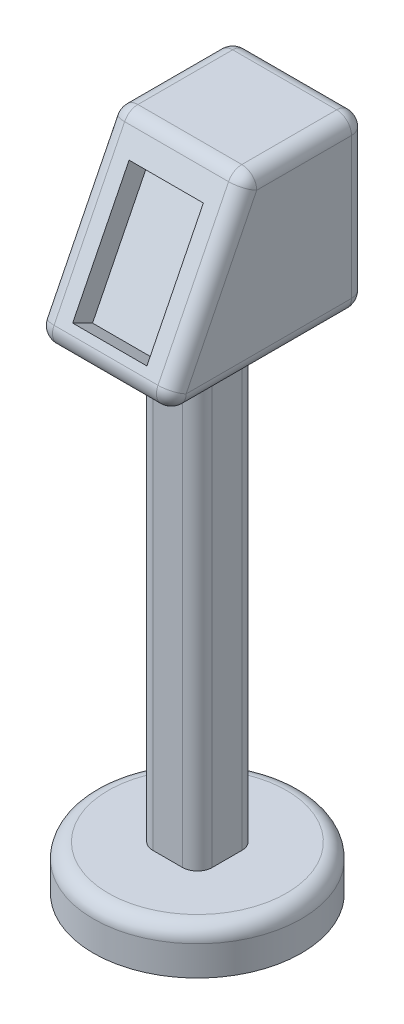
SolidWorks part; units mm, degrees
ref_plane "Front Plane" through (0, 0, 0) normal (0, 0, 1) x (1, 0, 0)
ref_plane "Top Plane" through (0, 0, 0) normal (0, 1, 0) x (1, 0, 0)
ref_plane "Right Plane" through (0, 0, 0) normal (1, 0, 0) x (0, 0, -1)
sketch "Sketch1" plane through (0, 0, 0) normal (0, 1, 0) x (1, 0, 0)
  circle A0 centre (0, 0) radius 140
  dimension "D1" = 280
extrude "Boss-Extrude1" add sketch "Sketch1" along normal blind 60
sketch "Sketch2" plane through (0, 60, 0) normal (0, 1, 0) x (1, 0, 0)
  line L1 (-40, 40) -> (40, 40)
  line L2 (-40, 40) -> (-40, -40)
  line L3 (-40, -40) -> (40, -40)
  line L4 (40, 40) -> (40, -40)
  line L5 (-40, 40) -> (40, -40) construction
  line L6 (-40, -40) -> (40, 40) construction
  point P0 (0, 0)
  dimension "D1" = 80
  dimension "D2" = 80
extrude "Boss-Extrude2" add sketch "Sketch2" along normal blind 600
sketch "Sketch3" plane through (0, 660, 0) normal (0, 1, 0) x (1, 0, 0)
  line L1 (-90, 137.5) -> (90, 137.5)
  line L2 (-90, 137.5) -> (-90, -137.5)
  line L3 (-90, -137.5) -> (90, -137.5)
  line L4 (90, 137.5) -> (90, -137.5)
  line L5 (-90, 137.5) -> (90, -137.5) construction
  line L6 (-90, -137.5) -> (90, 137.5) construction
  point P0 (0, 0)
  dimension "D1" = 275
  dimension "D2" = 180
extrude "Boss-Extrude3" add sketch "Sketch3" along normal blind 230
sketch "Sketch4" plane through (-90, 0, 0) normal (-1, 0, 0) x (0, 0, 1)
  line L0 (22.5, 890) -> (137.5, 660)
  line L1 (-137.5, 890) -> (137.5, 890) construction
  line L2 (137.5, 890) -> (137.5, 660) construction
  line L3 (137.5, 660) -> (137.5, 890)
  line L4 (137.5, 890) -> (22.5, 890)
  dimension "D1" = 160
  dimension "D2" = 0
extrude "Cut-Extrude1" cut sketch "Sketch4" against normal through all
sketch "Sketch5" plane through (0, 187, 374) normal (0, 0.4472, 0.8944) x (1, 0, 0)
  line L0 (-50, 742.4279) -> (-50, 572.4279)
  line L1 (-50, 572.4279) -> (50, 572.4279)
  line L2 (50, 572.4279) -> (50, 742.4279)
  line L3 (50, 742.4279) -> (-50, 742.4279)
  line L4 (90, 785.9779) -> (90, 528.8301) construction
  line L6 (90, 785.9779) -> (-90, 785.9779) construction
  dimension "D1" = 170
  dimension "D2" = 170
  dimension "D3" = 100
  dimension "D4" = 40
  dimension "D5" = 43.55
extrude "Cut-Extrude2" cut sketch "Sketch5" against normal blind 30 contours L2 L3 L0 L1
sketch "Sketch6" plane through (0, 173.5836, 347.1672) normal (0, 0.4472, 0.8944) x (1, 0, 0)
  line L0 (-50, 572.4279) -> (50, 572.4279) construction
  line L1 (-70, 762.4279) -> (70, 762.4279)
  line L2 (-70, 762.4279) -> (-70, 552.4279)
  line L3 (-70, 552.4279) -> (70, 552.4279)
  line L4 (70, 762.4279) -> (70, 552.4279)
  line L5 (-70, 762.4279) -> (70, 552.4279) construction
  line L6 (-70, 552.4279) -> (70, 762.4279) construction
  line L7 (50, 572.4279) -> (50, 742.4279) construction
  line L8 (90, 785.9779) -> (90, 528.8301) construction
  line L9 (-50, 742.4279) -> (-50, 572.4279) construction
  line L10 (50, 742.4279) -> (-50, 742.4279) construction
  point P0 (0, 657.4279)
  dimension "D1" = 20
  dimension "D2" = 20
  dimension "D3" = 20
  dimension "D4" = 20
  dimension "D5" = 20
extrude "Cut-Extrude3" cut sketch "Sketch6" against normal blind 15
fillet "Fillet1" radius 20 4 edges at (-40, 360, -40) (40, 360, -40) (40, 360, 40) (0, 60, 140)
fillet "Fillet2" radius 20 1 edges at (-40, 360, 40)
fillet "Fillet3" radius 20 12 edges at (90, 890, -57.5) (0, 890, 22.5) (90, 775, 80) (90, 775, -137.5) (90, 660, 0) (0, 660, -137.5) (0, 890, -137.5) (-90, 890, -57.5) (-90, 775, -137.5) (-90, 775, 80) (0, 660, 137.5) (-90, 660, 0)
